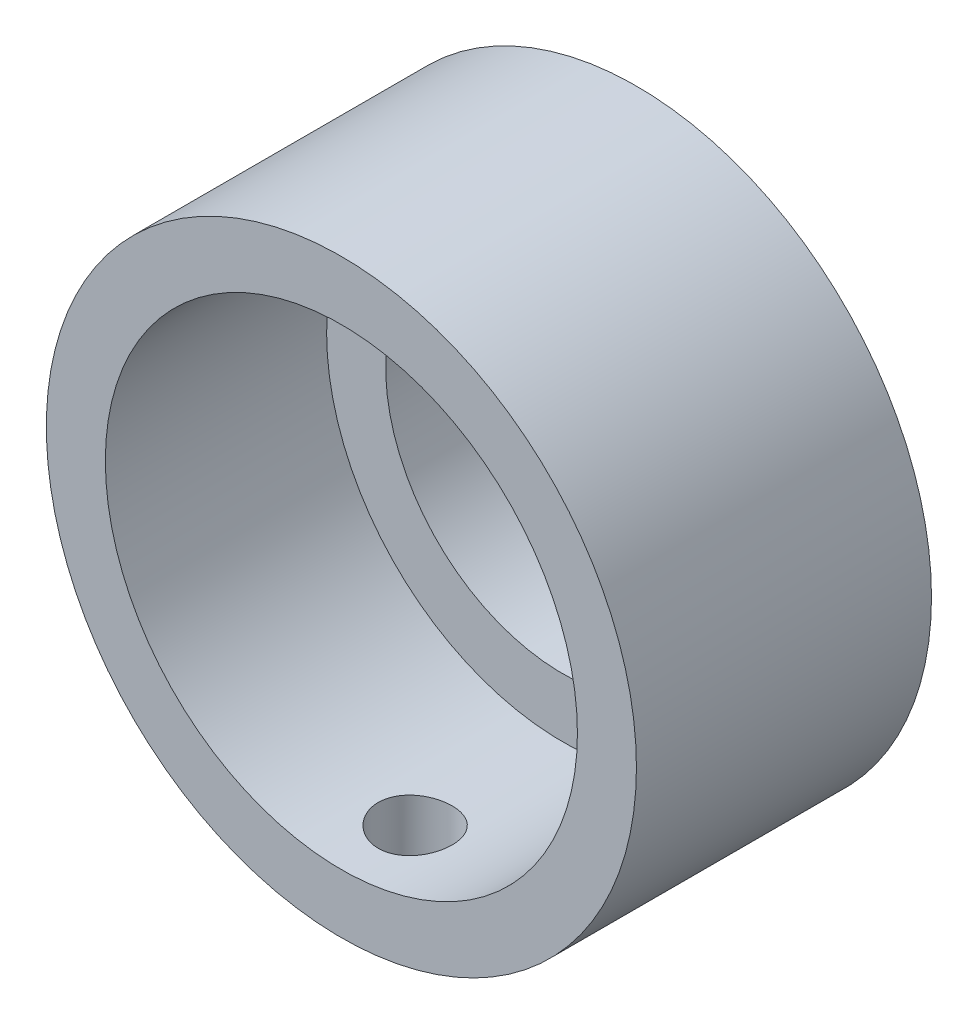
SolidWorks part; units mm, degrees
material "AISI 304"
ref_plane "前视基准面" through (0, 0, 0) normal (0, 0, 1) x (1, 0, 0)
ref_plane "上视基准面" through (0, 0, 0) normal (0, 1, 0) x (1, 0, 0)
ref_plane "右视基准面" through (0, 0, 0) normal (1, 0, 0) x (0, 0, -1)
sketch "草图2" plane through (0, 0, 0) normal (1, 0, 0) x (0, 0, -1)
  line L0 (0, 0) -> (10.5333, 0) construction
  line L1 (0, 3.2) -> (3, 3.2)
  line L2 (3, 3.2) -> (3, 2.4)
  line L3 (3, 2.4) -> (4, 2.4)
  line L4 (4, 2.4) -> (4, 4)
  line L5 (4, 4) -> (0, 4)
  line L6 (0, 4) -> (0, 3.2)
  dimension "D1" = 3.2
  dimension "D2" = 4
  dimension "D3" = 0.8
  dimension "D4" = 1
  dimension "D5" = 3
revolve "旋转1" add sketch "草图2" angle 360 about L0
sketch "草图3" plane through (0, 0, 0) normal (0, 1, 0) x (1, 0, 0)
  circle A0 centre (0, 1) radius 0.5
  dimension "D1" = 1
  dimension "D2" = 1
extrude "切除-拉伸1" cut sketch "草图3" against normal blind 10
